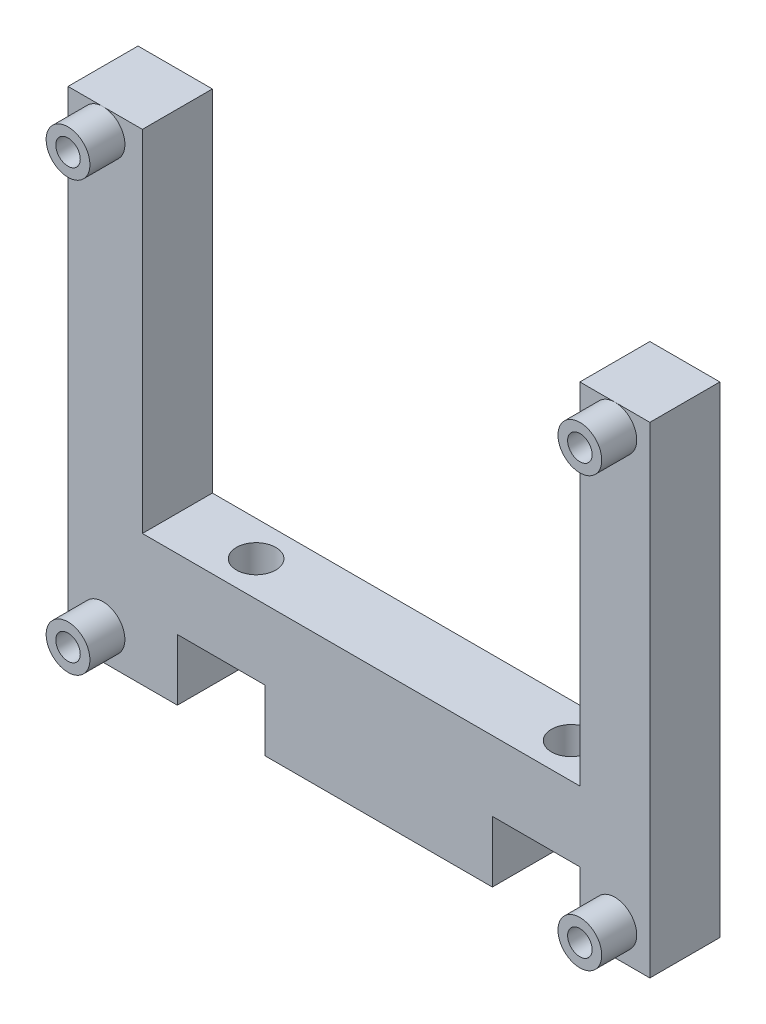
SolidWorks part; units mm, degrees
ref_plane "Piano frontale" through (0, 0, 0) normal (0, 0, 1) x (1, 0, 0)
ref_plane "Piano superiore" through (0, 0, 0) normal (0, 1, 0) x (1, 0, 0)
ref_plane "Piano destro" through (0, 0, 0) normal (1, 0, 0) x (0, 0, -1)
sketch "Schizzo1" plane through (0, 0, 0) normal (0, 0, 1) x (1, 0, 0)
  line L12 (-29.25, -24.5) -> (29.25, 24.5) construction
  line L13 (-29.25, -24.5) -> (29.25, -24.5) construction
  line L14 (-29.25, -24.5) -> (-29.25, 24.5) construction
  line L15 (-29.25, 24.5) -> (29.25, 24.5) construction
  line L16 (29.25, -24.5) -> (29.25, 24.5) construction
  circle A4 centre (-29.25, 24.5) radius 1.4
  circle A5 centre (29.25, 24.5) radius 1.4
  circle A6 centre (29.25, -24.5) radius 1.4
  circle A7 centre (-29.25, -24.5) radius 1.4
  circle A8 centre (-29.25, 24.5) radius 2.5
  circle A9 centre (29.25, 24.5) radius 2.5
  circle A10 centre (29.25, -24.5) radius 2.5
  circle A11 centre (-29.25, -24.5) radius 2.5
  dimension "D1" = 58.5
  dimension "D2" = 49
  dimension "D3" = 2.8
  dimension "D4" = 2.8
  dimension "D5" = 2.8
  dimension "D6" = 2.8
  dimension "D7" = 5
  dimension "D8" = 5
  dimension "D9" = 5
  dimension "D10" = 5
extrude "Estrusione-Estrusione1" add sketch "Schizzo1" along normal blind 4
sketch "Schizzo2" plane through (0, 0, 0) normal (0, 0, 1) x (1, 0, 0)
  line L0 (33.25, 27) -> (33.25, -28)
  line L4 (25.25, -13) -> (25.25, 27)
  line L5 (25.25, 27) -> (33.25, 27)
  line L6 (33.25, -28) -> (-33.25, -28)
  line L7 (-33.25, -28) -> (-33.25, 27)
  line L8 (-33.25, 27) -> (-24.75, 27)
  line L9 (-24.75, 27) -> (-24.75, -13)
  line L12 (-15.75, -12.3888) -> (-15.75, -28) construction
  line L13 (20.25, -12.3888) -> (20.25, -27.3888) construction
  line L14 (-24.75, -13) -> (25.25, -13)
  circle A0 centre (-29.25, 24.5) radius 1.4 construction
  circle A2 centre (29.25, 24.5) radius 1.4 construction
  dimension "D3" = 4
  dimension "D9" = 2.5
  dimension "D10" = 4
  dimension "D11" = 4
  dimension "D6" = 50
  dimension "D2" = 15
  dimension "D4" = 55
  dimension "D5" = 36
  dimension "D7" = 5
extrude "Estrusione-Estrusione2" add sketch "Schizzo2" against normal blind 8
sketch "Schizzo3" plane through (0, -28, 0) normal (0, -1, 0) x (1, 0, 0)
  line L0 (-15.75, 0) -> (-15.75, -8) construction
  line L1 (-33.25, -8) -> (33.25, -8) construction
  line L2 (-33.25, 0) -> (33.25, 0) construction
  line L6 (-33.25, 0) -> (33.25, 0) construction
  circle A0 centre (-15.75, -4) radius 2.25
  circle A1 centre (20.25, -4) radius 2.25
  dimension "D4" = 4.5
  dimension "D5" = 4.5
  dimension "D2" = 36
  dimension "D1" = 5
  dimension "D3" = 4
  dimension "D6" = 4
extrude "Taglio-Estrusione1" cut sketch "Schizzo3" against normal blind 18
sketch "Schizzo4" plane through (0, -28, 0) normal (0, -1, 0) x (1, 0, 0)
  line L0 (-33.25, 0) -> (33.25, 0) construction
  line L1 (-20.75, 0) -> (-10.75, 0)
  line L2 (-20.75, 0) -> (-20.75, -8)
  line L3 (-20.75, -8) -> (-10.75, -8)
  line L4 (-10.75, 0) -> (-10.75, -8)
  line L5 (-33.25, -8) -> (33.25, -8) construction
  line L6 (-20.75, -8) -> (-10.75, 0) construction
  line L7 (15.25, 0) -> (25.25, 0)
  line L8 (15.25, 0) -> (15.25, -8)
  line L9 (15.25, -8) -> (25.25, -8)
  line L10 (25.25, 0) -> (25.25, -8)
  line L11 (15.25, -8) -> (25.25, 0) construction
  circle A0 centre (20.25, -4) radius 2.25 construction
  circle A1 centre (-15.75, -4) radius 2.25 construction
  point P14 (20.25, -4)
  point P15 (-15.75, -4)
  dimension "D1" = 10
  dimension "D2" = 10
extrude "Taglio-Estrusione2" cut sketch "Schizzo4" against normal blind 7
